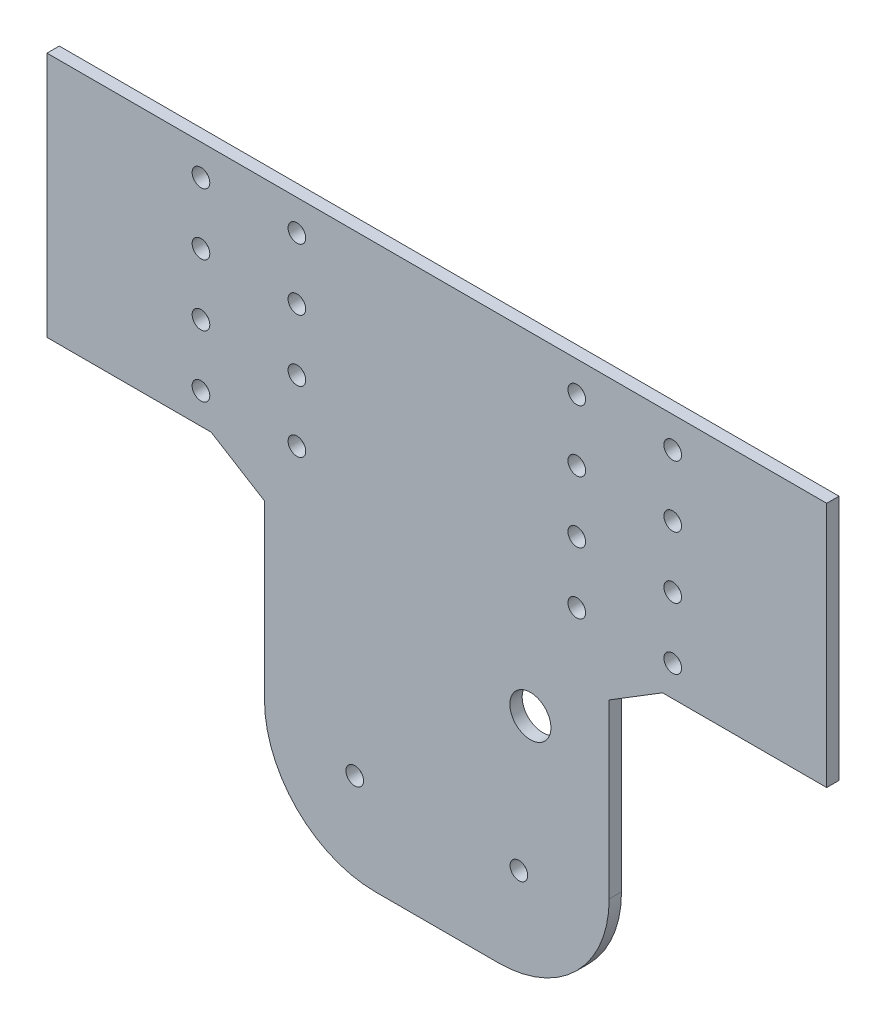
SolidWorks part; units mm, degrees
material "A-玻璃纤维"
ref_plane "前视基准面" through (0, 0, 0) normal (0, 0, 1) x (1, 0, 0)
ref_plane "上视基准面" through (0, 0, 0) normal (0, 1, 0) x (1, 0, 0)
ref_plane "右视基准面" through (0, 0, 0) normal (1, 0, 0) x (0, 0, -1)
other "Configuration Table"
sketch "草图1" plane through (0, 0, 0) normal (0, 0, 1) x (1, 0, 0)
  line L0 (0, 0) -> (0, -60)
  line L1 (0, -60) -> (53, -60)
  line L2 (53, -60) -> (53, -110)
  line L3 (53, -110) -> (137, -110) construction
  line L4 (137, -110) -> (137, -60)
  line L5 (137, -60) -> (190, -60)
  line L6 (190, -60) -> (190, 0)
  line L7 (190, 0) -> (0, 0)
  line L8 (95, -110) -> (95, 0) construction
  line L9 (80, -137) -> (110, -137)
  arc A0 (53, -110) -> (80, -137) centre (80, -110) ccw
  arc A1 (137, -110) -> (110, -137) centre (110, -110) cw
  dimension "D1" = 60
  dimension "D2" = 190
  dimension "D3" = 53
  dimension "D4" = 53
  dimension "D5" = 50
extrude "凸台-拉伸1" add sketch "草图1" along normal blind 3
sketch "草图2" plane through (0, 0, 3) normal (0, 0, 1) x (1, 0, 0)
  line L0 (95, 0) -> (95, -137) construction
  line L1 (190, 0) -> (0, 0) construction
  line L2 (80, -137) -> (110, -137) construction
  line L3 (59.4404, -115) -> (159.3721, -115) construction
  line L4 (137, -60) -> (190, -60) construction
  circle A0 centre (75, -115) radius 2.15
  circle A1 centre (115, -115) radius 2.15
  dimension "D2" = 4.3
  dimension "D1" = 55
  dimension "D3" = 40
extrude "切除-拉伸1" cut sketch "草图2" against normal up to next
chamfer "倒角1" distance 13 distance2 8 1 edges at (53, -60, 1.5)
chamfer "倒角2" distance 8 distance2 13 1 edges at (137, -60, 1.5)
sketch "草图4" plane through (0, 0, 0) normal (0, 0, -1) x (-1, 0, 0)
  circle A1 centre (-182, -52.5) radius 2.15
  circle A2 centre (-182, -52.5) radius 2.15
  circle A3 centre (-8, -22.5) radius 2.15
  circle A4 centre (-8, -22.5) radius 2.15
  circle A5 centre (-8, -7.5) radius 2.15
  circle A6 centre (-8, -7.5) radius 2.15
  circle A7 centre (-182, -7.5) radius 2.15
  circle A8 centre (-182, -7.5) radius 2.15
  circle A9 centre (-182, -22.5) radius 2.15
  circle A10 centre (-182, -22.5) radius 2.15
  circle A11 centre (-182, -37.5) radius 2.15
  circle A12 centre (-182, -37.5) radius 2.15
  circle A13 centre (-8, -52.5) radius 2.15
  circle A14 centre (-8, -52.5) radius 2.15
  circle A15 centre (-8, -37.5) radius 2.15
  circle A16 centre (-8, -37.5) radius 2.15
  dimension "D1" = 0
  dimension "D2" = 0
  dimension "D3" = 0
  dimension "D4" = 0
  dimension "D5" = 0
  dimension "D6" = 0
  dimension "D7" = 0
  dimension "D8" = 0
sketch "草图5" plane through (0, 0, 0) normal (0, 0, -1) x (-1, 0, 0)
  circle A1 centre (-31.3751, -37.5) radius 2.15
  circle A2 centre (-31.3751, -37.5) radius 2.15
  circle A3 centre (-31.3751, -52.5) radius 2.15
  circle A4 centre (-31.3751, -52.5) radius 2.15
  circle A5 centre (-158.6249, -7.5) radius 2.15
  circle A6 centre (-158.6249, -7.5) radius 2.15
  circle A7 centre (-31.3751, -7.5) radius 2.15
  circle A8 centre (-31.3751, -7.5) radius 2.15
  circle A9 centre (-31.3751, -22.5) radius 2.15
  circle A10 centre (-31.3751, -22.5) radius 2.15
  circle A11 centre (-158.6249, -52.5) radius 2.15
  circle A12 centre (-158.6249, -52.5) radius 2.15
  circle A13 centre (-158.6249, -37.5) radius 2.15
  circle A14 centre (-158.6249, -37.5) radius 2.15
  circle A15 centre (-158.6249, -22.5) radius 2.15
  circle A16 centre (-158.6249, -22.5) radius 2.15
  dimension "D1" = 0
  dimension "D2" = 0
  dimension "D3" = 0
  dimension "D4" = 0
  dimension "D5" = 0
  dimension "D6" = 0
  dimension "D7" = 0
  dimension "D8" = 0
sketch "草图6" plane through (0, 0, 0) normal (0, 0, -1) x (-1, 0, 0)
  circle A2 centre (-117.7908, -81) radius 5
  dimension "D1" = 10
extrude "切除-拉伸4" cut sketch "草图6" against normal blind 10
sketch "草图7" plane through (0, 0, 0) normal (0, 0, -1) x (-1, 0, 0)
  line L0 (-190, 0) -> (0, 0) construction
  line L1 (-95, 0) -> (-95, 50000) construction
  line L2 (-140.79, 23.2902) -> (-140.79, -79.9473) construction
  line L3 (-49.21, 23.2902) -> (-49.21, -94.7438) construction
  circle A0 centre (-129.1, -7.5) radius 2.15
  circle A2 centre (-152.48, -7.5) radius 2.15
  circle A3 centre (-152.48, -22.5) radius 2.15
  circle A4 centre (-129.1, -22.5) radius 2.15
  circle A5 centre (-152.48, -37.5) radius 2.15
  circle A6 centre (-129.1, -37.5) radius 2.15
  circle A7 centre (-152.48, -52.5) radius 2.15
  circle A8 centre (-129.1, -52.5) radius 2.15
  circle A9 centre (-60.9, -22.5) radius 2.15
  circle A10 centre (-37.52, -22.5) radius 2.15
  circle A11 centre (-60.9, -37.5) radius 2.15
  circle A12 centre (-37.52, -37.5) radius 2.15
  circle A13 centre (-60.9, -52.5) radius 2.15
  circle A14 centre (-37.52, -52.5) radius 2.15
  circle A15 centre (-60.9, -7.5) radius 2.15
  circle A16 centre (-37.52, -7.5) radius 2.15
  point P2 (-95, 0)
  dimension "D3" = 4.3
  dimension "D4" = 23.38
  dimension "D1" = 45.79
  dimension "D2" = 91.58
  dimension "D5" = 4
  dimension "D6" = 2
extrude "切除-拉伸5" cut sketch "草图7" against normal through all
